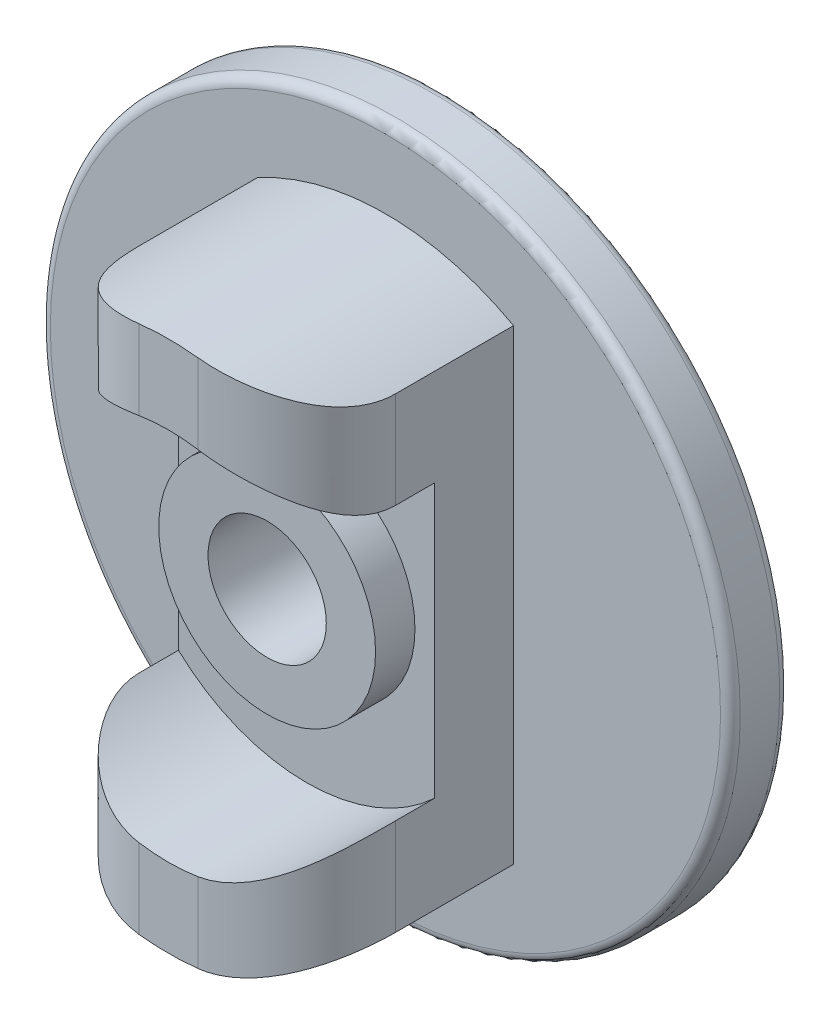
SolidWorks part; units mm, degrees
material "Cast Alloy Steel"
ref_plane "Front" through (0, 0, 0) normal (0, 0, 1) x (1, 0, 0)
ref_plane "Top" through (0, 0, 0) normal (0, 1, 0) x (1, 0, 0)
ref_plane "Right" through (0, 0, 0) normal (1, 0, 0) x (0, 0, -1)
sketch "Sketch1" plane through (0, 0, 0) normal (0, 0, 1) x (1, 0, 0)
  circle A0 centre (0, 0) radius 17.5
extrude "Boss-Extrude1" add sketch "Sketch1" along normal blind 3
sketch "Sketch2" plane through (0, 0, 0) normal (0, 0, -1) x (-1, 0, 0)
  circle A0 centre (0, 0) radius 15.5
extrude "Cut-Extrude1" cut sketch "Sketch2" against normal blind 1
sketch "Sketch3" plane through (0, 0, 3) normal (0, 0, 1) x (1, 0, 0)
  line L1 (-6.5, 14) -> (6.5, 14)
  line L2 (-6.5, 14) -> (-6.5, -14)
  line L3 (-6.5, -14) -> (6.5, -14)
  line L4 (6.5, 14) -> (6.5, -14)
  line L5 (-6.5, 14) -> (6.5, -14) construction
  line L6 (-6.5, -14) -> (6.5, 14) construction
  point P0 (0, 0)
  dimension "D1" = 13
  dimension "D2" = 28
extrude "Boss-Extrude2" add sketch "Sketch3" along normal blind 11
sketch "Sketch4" plane through (0, 0, 14) normal (0, 0, 1) x (1, 0, 0)
  circle A0 centre (0, 0) radius 9.5
extrude "Cut-Extrude2" cut sketch "Sketch4" against normal blind 7
sketch "Sketch5" plane through (0, 0, 14) normal (0, 0, 1) x (1, 0, 0)
  circle A0 centre (0, 0) radius 13.5
  circle A1 centre (0, 0) radius 16.5421
extrude "Cut-Extrude3" cut sketch "Sketch5" against normal blind 11
fillet "Fillet1" radius 5 4 edges at (-6.5, -9.3802, 14) (-6.5, 9.3802, 14) (6.5, 9.3802, 14) (6.5, -9.3802, 14)
sketch "Sketch6" plane through (0, 0, 7) normal (0, 0, 1) x (1, 0, 0)
  circle A0 centre (0, 0) radius 5.5
extrude "Boss-Extrude3" add sketch "Sketch6" along normal blind 2
sketch "Sketch7" plane through (0, 0, 9) normal (0, 0, 1) x (1, 0, 0)
  circle A0 centre (0, 0) radius 3
extrude "Cut-Extrude4" cut sketch "Sketch7" against normal through all
fillet "Fillet3" radius 0.5 3 edges at (-15.5, 0, 0) (17.5, 0, 0) (17.5, 0, 3)
